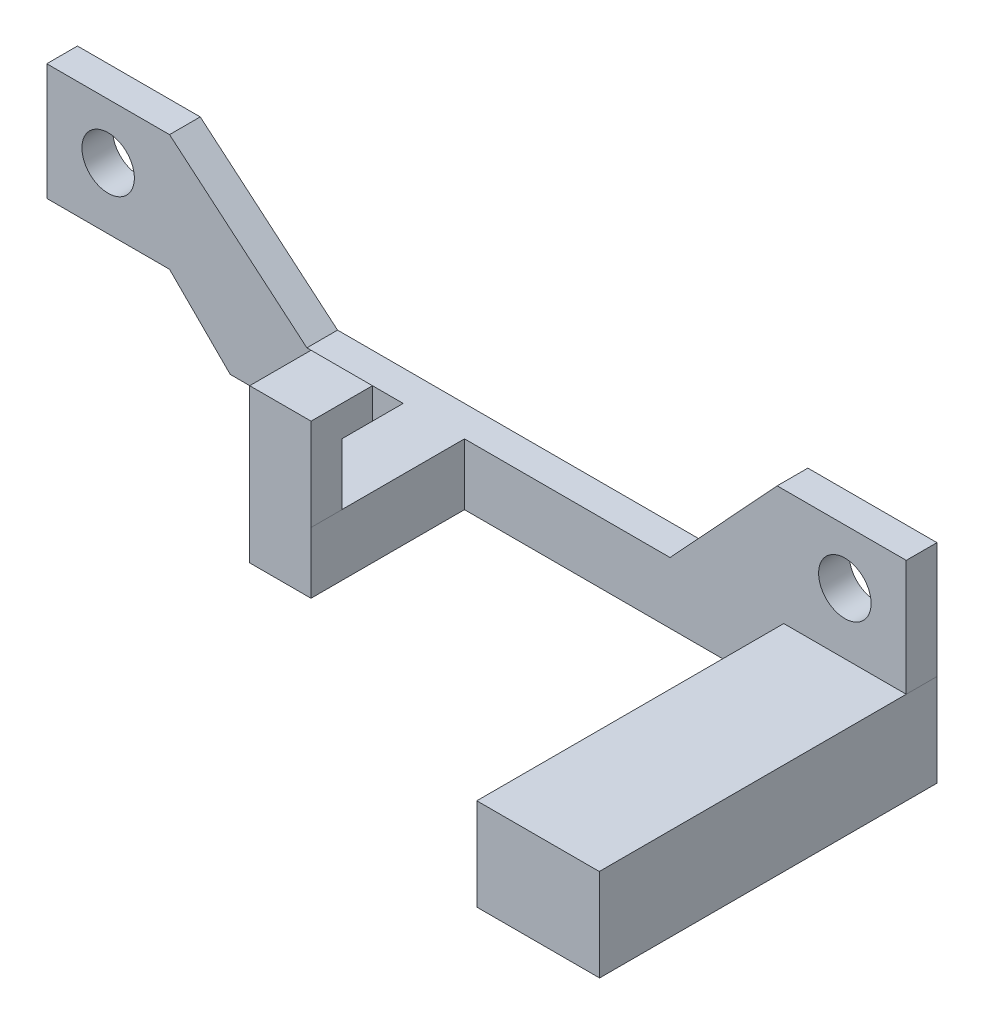
SolidWorks part; units mm, degrees
ref_plane "Front Plane" through (0, 0, 0) normal (0, 0, 1) x (1, 0, 0)
ref_plane "Top Plane" through (0, 0, 0) normal (0, 1, 0) x (1, 0, 0)
ref_plane "Right Plane" through (0, 0, 0) normal (1, 0, 0) x (0, 0, -1)
sketch "Sketch1" plane through (0, 0, 0) normal (0, 0, 1) x (1, 0, 0)
  line L3 (5.08, -5.08) -> (-5.08, -5.08)
  line L9 (66.04, -5.0526) -> (55.9053, -5.0526)
  line L15 (5.08, -5.08) -> (10.1021, -10.1021)
  line L16 (10.1021, -10.1021) -> (51.2288, -10.1021)
  line L17 (51.2288, -10.1021) -> (55.9053, -5.0526)
  line L19 (66.04, -5.0526) -> (66.04, 4.544)
  line L21 (46.4986, -5.0253) -> (16.4443, -5.0253)
  line L22 (66.04, 4.544) -> (55.3584, 4.544)
  line L23 (55.3584, 4.544) -> (46.4986, -5.0253)
  line L24 (-5.08, -5.08) -> (-5.08, 4.572)
  line L25 (-5.08, 4.572) -> (5.08, 4.572)
  line L26 (5.08, 4.572) -> (16.4443, -5.0253)
  circle A0 centre (0, 0) radius 2.1717
  circle A1 centre (60.96, 0) radius 2.1717
extrude "Boss-Extrude2" add sketch "Sketch1" along normal blind 2.54
sketch "Sketch2" plane through (0, 0, 2.54) normal (0, 0, 1) x (1, 0, 0)
  line L0 (55.9053, -5.0526) -> (55.9053, -12.6726)
  line L1 (55.9053, -12.6726) -> (66.0653, -12.6726)
  line L2 (66.04, -5.0526) -> (66.0653, -12.6726)
  line L3 (66.04, -5.0526) -> (55.9053, -5.0526)
extrude "Boss-Extrude3" add sketch "Sketch2" along normal blind 25.4 and the other way blind 2.54
sketch "Sketch3" plane through (0, 0, 2.54) normal (0, 0, 1) x (1, 0, 0)
  line L0 (24.4116, -5.0253) -> (24.4116, -10.1021)
  line L1 (46.4986, -5.0253) -> (16.4443, -5.0253) construction
  line L2 (10.1021, -10.1021) -> (51.2288, -10.1021) construction
  line L3 (24.4116, -10.1021) -> (29.486, -10.1021)
  line L4 (29.486, -10.1021) -> (29.486, -5.0253)
  line L5 (29.486, -5.0253) -> (24.4116, -5.0253)
extrude "Boss-Extrude4" add sketch "Sketch3" along normal blind 12.7
sketch "Sketch5" plane through (24.4116, 0, 0) normal (-1, 0, 0) x (0, 0, 1)
  line L0 (15.24, -5.0253) -> (15.24, 2.5947)
  line L1 (15.24, 2.5947) -> (12.6998, 2.5947)
  line L2 (12.6998, 2.5947) -> (10.1598, 2.5947)
  line L3 (10.1598, 2.5947) -> (10.1598, 0.0547)
  line L4 (10.1598, 0.0547) -> (12.6998, 0.0547)
  line L5 (12.6998, 0.0547) -> (12.6998, -5.0253)
  line L6 (15.24, -5.0253) -> (2.54, -5.0253) construction
  line L7 (15.24, -5.0253) -> (12.6998, -5.0253)
extrude "Boss-Extrude5" add sketch "Sketch5" against normal blind 5.08
